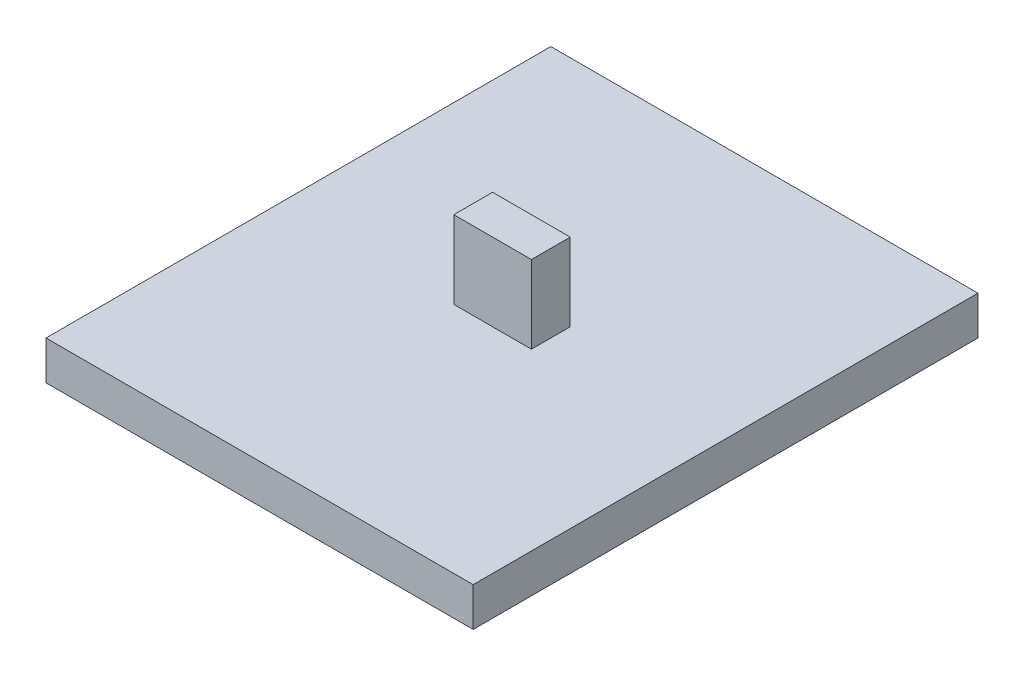
SolidWorks part; units mm, degrees
ref_plane "Front Plane" through (0, 0, 0) normal (0, 0, 1) x (1, 0, 0)
ref_plane "Top Plane" through (0, 0, 0) normal (0, 1, 0) x (1, 0, 0)
ref_plane "Right Plane" through (0, 0, 0) normal (1, 0, 0) x (0, 0, -1)
sketch "Sketch1" plane through (0, 0, 0) normal (0, 0, 1) x (1, 0, 0)
  line L2 (55, 0) -> (-55, 0) construction
  line L4 (34.925, 0) -> (34.925, 6.35)
  line L5 (34.925, 6.35) -> (-34.925, 6.35)
  line L6 (-34.925, 6.35) -> (-34.925, 0)
  line L9 (0, 3.81) -> (0, 0) construction
  line L10 (-34.925, 0) -> (34.925, 0)
  point P3 (0, 3.81)
  dimension "D5" = 69.85
  dimension "D1" = 6.35
extrude "Boss-Extrude1" add sketch "Sketch1" along normal mid plane 82.55
shell "Shell1" thickness 2.54
sketch "Sketch2" plane through (0, 0, 0) normal (0, 0, 1) x (1, 0, 0)
  line L0 (-6.35, 6.35) -> (6.35, 6.35)
  line L1 (34.925, 6.35) -> (-34.925, 6.35) construction
  line L2 (6.35, 6.35) -> (6.35, 19.05)
  line L3 (6.35, 19.05) -> (-6.35, 19.05)
  line L4 (-6.35, 19.05) -> (-6.35, 6.35)
  point P5 (0, 6.35)
  point P7 (0, 0)
  point P8 (0, 6.35)
  point P10 (0, 0)
  dimension "D1" = 12.7
  dimension "D2" = 12.7
extrude "Boss-Extrude2" add sketch "Sketch2" along normal mid plane 6.35
equation "\"Lid L\"= 3.25"
equation "\"Lid W\"= 2.75"
equation "\"Lid H\"= .25"
equation "\"D1@Boss-Extrude1\"=\"Lid L\""
equation "\"D5@Sketch1\"=\"Lid W\""
equation "\"D1@Sketch1\"=\"Lid H\""
equation "\"Walls\"= .1"
equation "\"D1@Shell1\"=\"Walls\""
equation "\"Handle L\"= .5"
equation "\"Handle W\"= .25"
equation "\"Handle H\"= .5"
equation "\"D1@Sketch2\"=\"Handle L\""
equation "\"D2@Sketch2\"=\"Handle H\" "
equation "\"D1@Boss-Extrude2\"=\"Handle W\""
